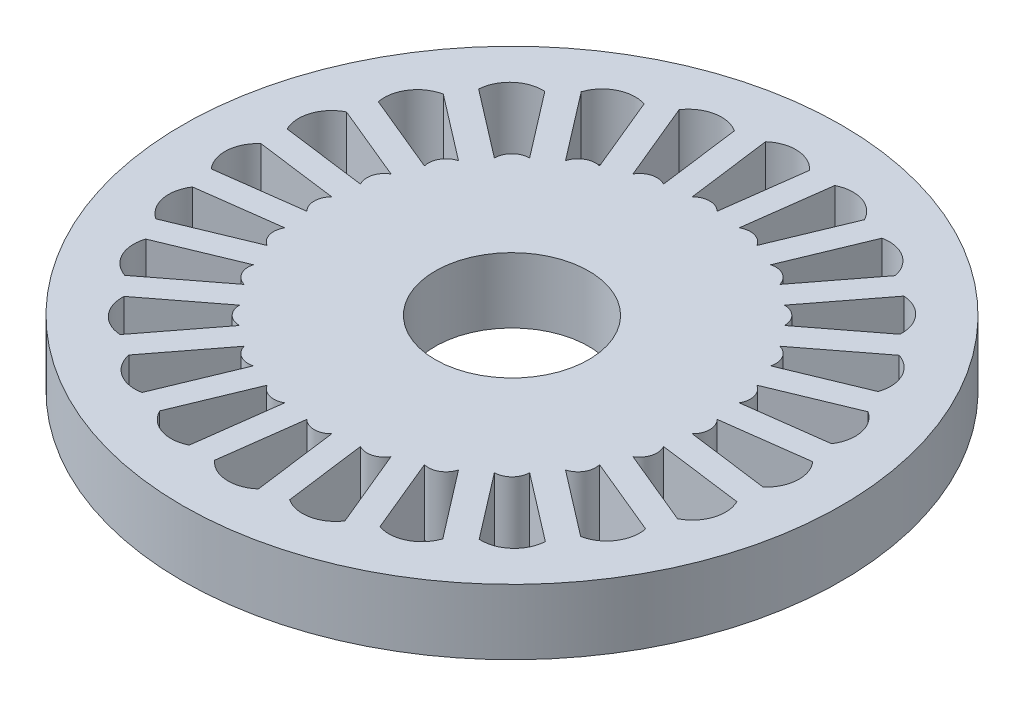
SolidWorks part; units mm, degrees
ref_plane "Front Plane" through (0, 0, 0) normal (0, 0, 1) x (1, 0, 0)
ref_plane "Top Plane" through (0, 0, 0) normal (0, 1, 0) x (1, 0, 0)
ref_plane "Right Plane" through (0, 0, 0) normal (1, 0, 0) x (0, 0, -1)
sketch "Sketch2" plane through (0, 0, 0) normal (0, 1, 0) x (1, 0, 0)
  circle A0 centre (0, 0) radius 12.875
  circle A1 centre (0, 0) radius 3
  dimension "D1" = 25.75
  dimension "D2" = 6
extrude "Boss-Extrude1" add sketch "Sketch2" along normal blind 2.55
sketch "Sketch4" plane through (0, 2.55, 0) normal (0, 1, 0) x (1, 0, 0)
  line L1 (0, 7.7301) -> (0, 11.1513) construction
  line L3 (0.4868, 7.5284) -> (0.9065, 10.716)
  line L4 (-0.4868, 7.5284) -> (-0.9212, 10.8278)
  arc A1 (-0.9212, 10.8278) -> (0.9065, 10.716) centre (-0.0633, 9.8581) cw
  arc A2 (-0.4868, 7.5284) -> (0.4868, 7.5284) centre (0, 7.0416) cw
extrude "Cut-Extrude1" cut sketch "Sketch4" against normal blind 2.55
pattern_circular "CirPattern1" count 24 over 360 about axis through (0, 0, 0) along (0, 1, 0) of "Cut-Extrude1"
